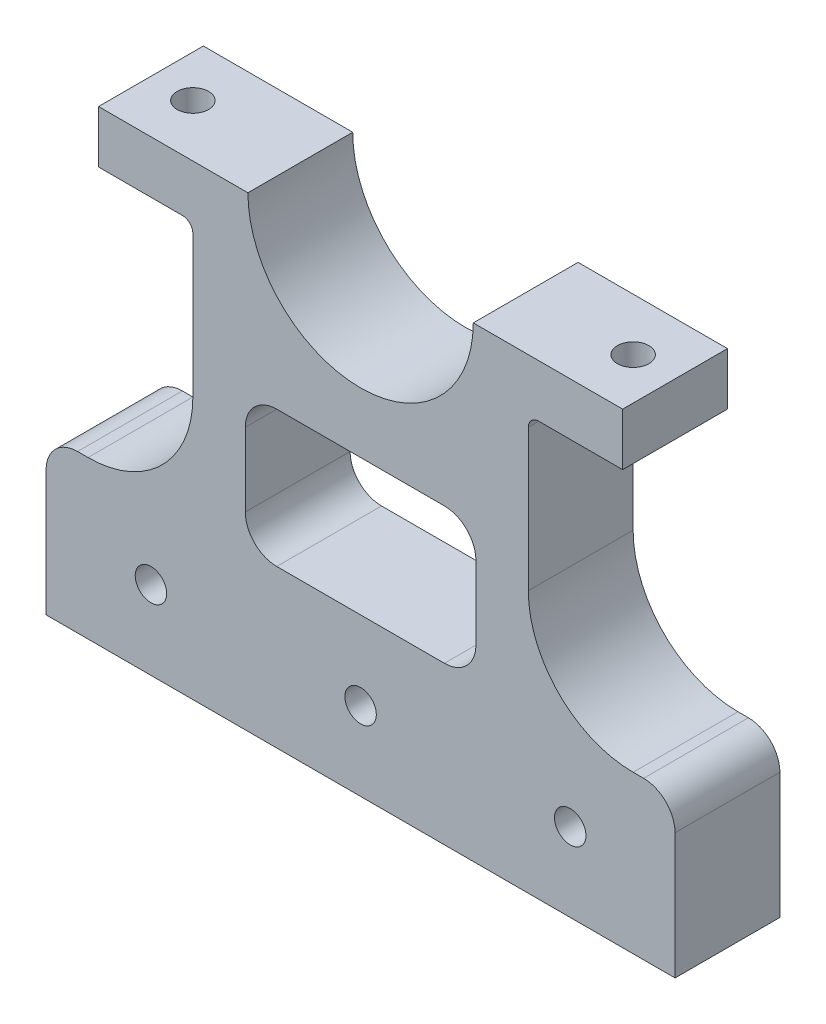
SolidWorks part; units mm, degrees
material "POM 乙缩醛共聚物"
ref_plane "前视基准面" through (0, 0, 0) normal (0, 0, 1) x (1, 0, 0)
ref_plane "上视基准面" through (0, 0, 0) normal (0, 1, 0) x (1, 0, 0)
ref_plane "右视基准面" through (0, 0, 0) normal (1, 0, 0) x (0, 0, -1)
sketch "草图2" plane through (0, 0, 0) normal (0, 0, 1) x (1, 0, 0)
  line L0 (0, 0) -> (0, 53.6154) construction
  line L1 (30, 0) -> (-30, 0)
  line L2 (-30, 0) -> (-30, 15)
  line L3 (30, 0) -> (30, 15)
  line L4 (-30, 15) -> (-16, 15)
  line L5 (30, 15) -> (16, 15)
  line L6 (-16, 15) -> (-16, 44.5)
  line L7 (16, 15) -> (16, 44.5)
  line L8 (-16, 44.5) -> (16, 44.5)
  point P12 (0, 44.5)
  dimension "D1" = 15
  dimension "D2" = 60
  dimension "D3" = 32
  dimension "D4" = 44.5
extrude "凸台-拉伸1" add sketch "草图2" along normal blind 10
sketch "草图3" plane through (0, 0, 10) normal (0, 0, 1) x (1, 0, 0)
  line L0 (16, 44.5) -> (-16, 44.5) construction
  circle A0 centre (0, 44.5) radius 10.75
  dimension "D1" = 21.5
extrude "切除-拉伸1" cut sketch "草图3" against normal through all contours A0
sketch "草图4" plane through (0, 0, 10) normal (0, 0, 1) x (1, 0, 0)
  line L0 (-30, 7.5) -> (30, 7.5) construction
  line L1 (-30, 15) -> (-30, 0) construction
  line L2 (30, 0) -> (30, 15) construction
  circle A0 centre (-20, 7.5) radius 1.5
  circle A1 centre (0, 7.5) radius 1.5
  circle A2 centre (20, 7.5) radius 1.5
  dimension "D1" = 20
  dimension "D3" = 3
  dimension "D2" = 20
extrude "切除-拉伸2" cut sketch "草图4" against normal through all
fillet "圆角1" radius 10 2 edges at (16, 15, 5) (-16, 15, 5)
fillet "圆角3" radius 3 2 edges at (-30, 15, 5) (30, 15, 5)
sketch "草图7" plane through (0, 0, 10) normal (0, 0, 1) x (1, 0, 0)
  line L0 (0, 0) -> (0, 44.6412) construction
  line L1 (-30, 0) -> (30, 0) construction
  line L2 (-11, 28) -> (11, 28)
  line L3 (-11, 28) -> (-11, 15)
  line L4 (-11, 15) -> (11, 15)
  line L5 (11, 28) -> (11, 15)
  line L6 (-11, 28) -> (11, 15) construction
  line L7 (-11, 15) -> (11, 28) construction
  point P3 (0, 21.5)
  dimension "D1" = 22
  dimension "D2" = 13
  dimension "D3" = 15
extrude "切除-拉伸5" cut sketch "草图7" against normal through all
fillet "圆角4" radius 3 4 edges at (-11, 15, 5) (11, 15, 5) (11, 28, 5) (-11, 28, 5)
sketch "草图8" plane through (0, 0, 10) normal (0, 0, 1) x (1, 0, 0)
  line L0 (0, 0) -> (0, 44.957) construction
  line L1 (25, 44.5) -> (25, 39.5)
  line L2 (-16, 44.5) -> (-25, 44.5)
  line L3 (-16, 44.5) -> (-16, 39.5)
  line L4 (-16, 39.5) -> (-25, 39.5)
  line L5 (-25, 44.5) -> (-25, 39.5)
  line L6 (16, 39.5) -> (25, 39.5)
  line L7 (16, 44.5) -> (16, 39.5)
  line L8 (16, 44.5) -> (25, 44.5)
  dimension "D1" = 9
  dimension "D2" = 5
extrude "凸台-拉伸2" add sketch "草图8" against normal up to surface (10 mm away) up to face at (0, 21.5, 0)
fillet "圆角5" radius 1 2 edges at (16, 39.5, 5) (-16, 39.5, 5)
sketch "草图9" plane through (0, 44.5, 0) normal (0, 1, 0) x (1, 0, 0)
  line L0 (-25, -5) -> (25, -5) construction
  line L1 (-25, 0) -> (-25, -10) construction
  line L2 (25, 0) -> (25, -10) construction
  line L3 (0, -5) -> (0, 0) construction
  circle A0 centre (-21, -5) radius 1.5
  circle A1 centre (21, -5) radius 1.5
  dimension "D1" = 4
  dimension "D2" = 3
extrude "切除-拉伸6" cut sketch "草图9" against normal up to surface (5 mm away) up to face at (-21, 39.5, 5)
